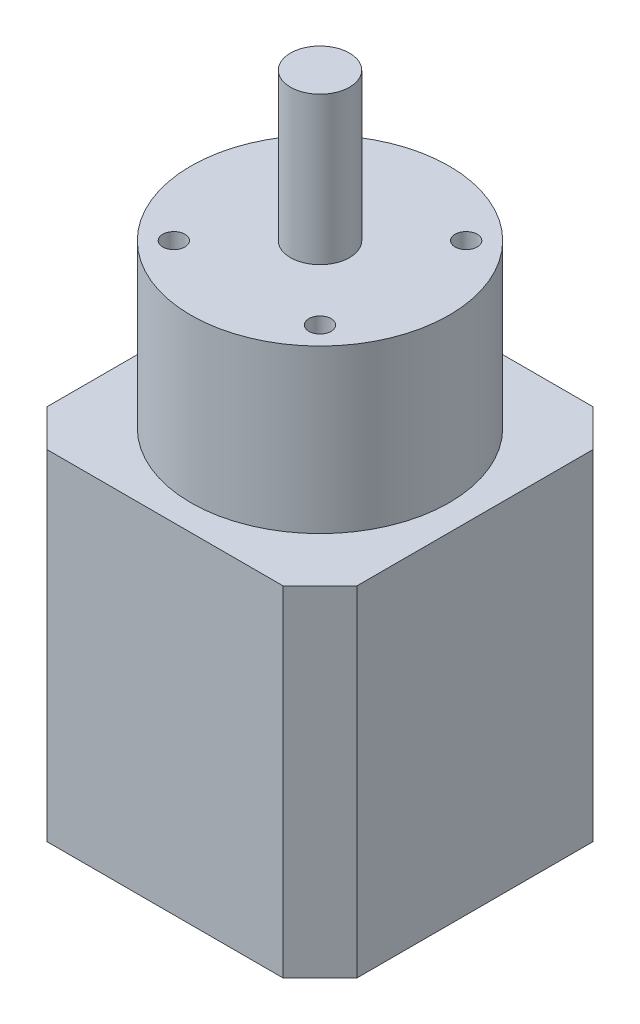
SolidWorks part; units mm, degrees
material "6061 Alloy"
ref_plane "Front Plane" through (0, 0, 0) normal (0, 0, 1) x (1, 0, 0)
ref_plane "Top Plane" through (0, 0, 0) normal (0, 1, 0) x (1, 0, 0)
ref_plane "Right Plane" through (0, 0, 0) normal (1, 0, 0) x (0, 0, -1)
sketch "Sketch1" plane through (0, 0, 0) normal (0, 1, 0) x (1, 0, 0)
  line L1 (-21, -21) -> (21, -21)
  line L2 (-21, -21) -> (-21, 21)
  line L3 (-21, 21) -> (21, 21)
  line L4 (21, -21) -> (21, 21)
  line L5 (-21, -21) -> (21, 21) construction
  line L6 (-21, 21) -> (21, -21) construction
  point P0 (0, 0)
  dimension "D1" = 42
  dimension "D2" = 42
extrude "Boss-Extrude1" add sketch "Sketch1" along normal blind 46
chamfer "Chamfer1" distance 5 angle 45 4 edges at (-21, 23, -21) (21, 23, -21) (21, 23, 21) (-21, 23, 21)
sketch "Sketch5" plane through (0, 46, 0) normal (0, 1, 0) x (1, 0, 0)
  circle A0 centre (0, 0) radius 17.5
  dimension "D1" = 35
extrude "Boss-Extrude4" add sketch "Sketch5" along normal blind 22
sketch "Sketch6" plane through (0, 68, 0) normal (0, 1, 0) x (1, 0, 0)
  circle A0 centre (0, 0) radius 4
  dimension "D1" = 8
extrude "Boss-Extrude5" add sketch "Sketch6" along normal blind 20
sketch "Sketch7" plane through (0, 68, 0) normal (0, 1, 0) x (1, 0, 0)
  line L0 (-9.8995, -9.8995) -> (-9.8995, 9.8995) construction
  line L1 (-9.8995, 9.8995) -> (9.8995, 9.8995) construction
  circle A0 centre (0, 0) radius 14 construction
  circle A1 centre (-9.8995, 9.8995) radius 1.5
  circle A2 centre (9.8995, 9.8995) radius 1.5
  circle A3 centre (9.8995, -9.8995) radius 1.5
  circle A4 centre (-9.8995, -9.8995) radius 1.5
  dimension "D1" = 3
  dimension "D2" = 28
extrude "Cut-Extrude2" cut sketch "Sketch7" against normal blind 5
